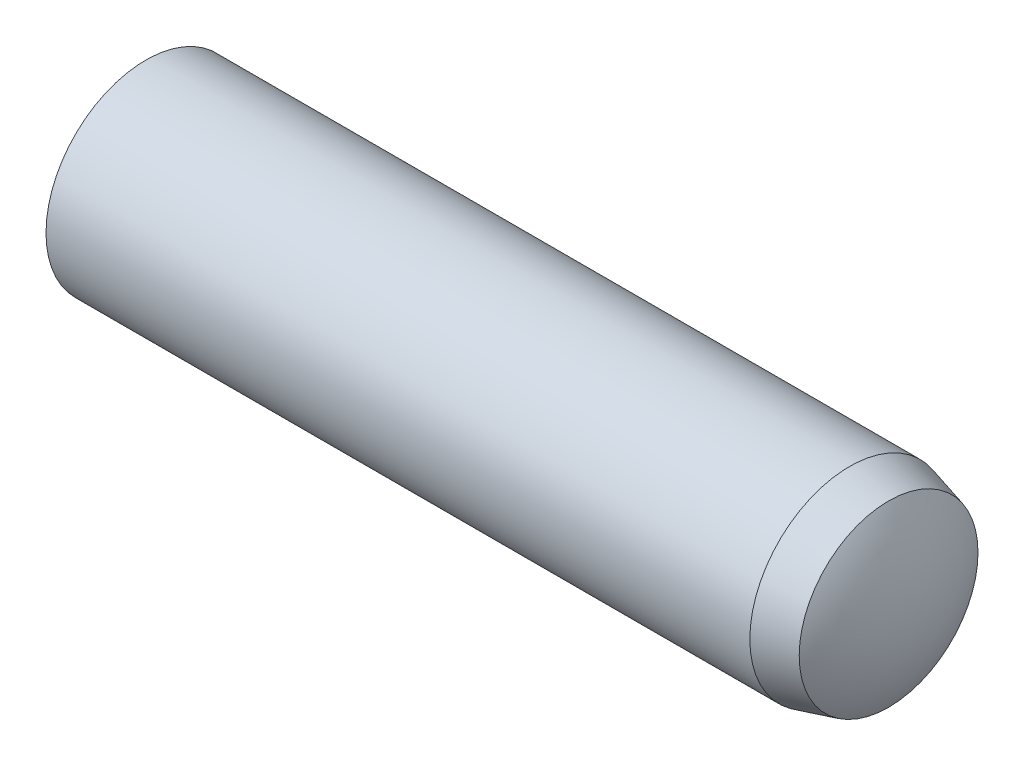
SolidWorks part; units mm, degrees
ref_plane "Front Plane" through (0, 0, 0) normal (0, 0, 1) x (1, 0, 0)
ref_plane "Top Plane" through (0, 0, 0) normal (0, 1, 0) x (1, 0, 0)
ref_plane "Right Plane" through (0, 0, 0) normal (1, 0, 0) x (0, 0, -1)
sketch "Sketch1" plane through (0, 0, 0) normal (0, 0, 1) x (1, 0, 0)
  line L0 (-5, 0) -> (5, 0) construction
  line L1 (5, 1.25) -> (5, -1.25) construction
  line L2 (-5, 1.25) -> (-5, -1.25) construction
  line L3 (4.1875, 1.25) -> (4.1875, -1.25) construction
  line L4 (-4.625, 1.25) -> (-4.625, -1.25) construction
  line L5 (-5, 0) -> (-4.625, 0) construction
  line L6 (5, 0) -> (4.1875, 0) construction
  line L7 (4.675, 1.25) -> (4.675, -1.25) construction
  dimension "Dia" = 2.5
  dimension "Length" = 10
  dimension "D1" = 0.8125
  dimension "D2" = 0.375
  dimension "D3" = 0.4875
sketch "Sketch2" plane through (0, 0, 0) normal (1, 0, 0) x (0, 0, -1)
  circle A0 centre (0, 0) radius 1.25
extrude "Extrude1" add sketch "Sketch2" against normal up to vertex (5 mm away) and the other way up to vertex (5 mm away) up to point (-5, 0, 0) other way up to point (5, 0, 0)
sketch "Sketch5" plane through (0, 0, 0) normal (0, 0, 1) x (1, 0, 0)
  line L0 (4.1875, 1.25) -> (4.1875, 1.75)
  line L1 (4.1875, 1.75) -> (5.5, 1.75)
  line L2 (5.5, 1.75) -> (5.5, 0)
  line L3 (5, 0) -> (5.5, 0)
  line L5 (-4.625, 1.25) -> (-4.625, 1.75)
  line L6 (-4.625, 1.75) -> (-5.5, 1.75)
  line L7 (-5.5, 1.75) -> (-5.5, 0)
  line L8 (4.1875, 1.25) -> (4.675, 1.1194)
  line L10 (-5, 0) -> (-5.5, 0)
  line L11 (-5, 1.25) -> (-5, -1.25) construction
  line L13 (4.1875, 1.25) -> (4.1875, -1.25) construction
  line L15 (-5, 0) -> (5, 0) construction
  line L16 (4.675, 1.25) -> (4.675, -1.25) construction
  line L17 (5, 1.25) -> (5, -1.25) construction
  arc A0 (4.675, 1.1194) -> (5, 0) centre (2.9098, 0) cw
  arc A1 (-4.625, 1.25) -> (-5, 0) centre (-2.7292, 0) ccw
  dimension "D1" = 15
  dimension "D2" = 0.5
revolve "Cut-Revolve1" cut sketch "Sketch5" angle 360 about L0
equation "\"D1@Sketch1\" = \"Dia@Sketch1\"*.325"
equation "\"D2@Sketch1\" = \"Dia@Sketch1\"*.15"
equation "\"D3@Sketch1\" = \"D1@Sketch1\"*.6"
